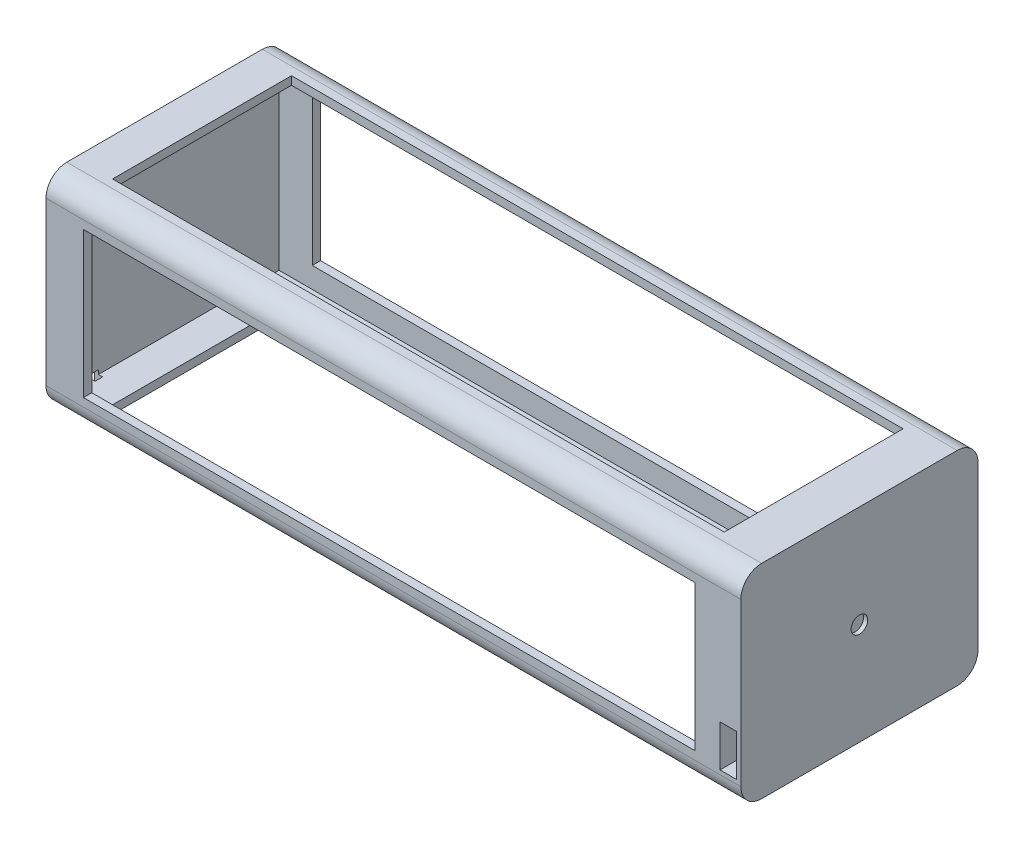
SolidWorks part; units mm, degrees
material "PET"
ref_plane "Спереди" through (0, 0, 0) normal (0, 0, 1) x (1, 0, 0)
ref_plane "Сверху" through (0, 0, 0) normal (0, 1, 0) x (1, 0, 0)
ref_plane "Справа" through (0, 0, 0) normal (1, 0, 0) x (0, 0, -1)
sketch "Эскиз1" plane through (0, 0, 0) normal (1, 0, 0) x (0, 0, -1)
  line L1 (26.5, -22.5) -> (-26.5, -22.5)
  line L2 (26.5, -22.5) -> (26.5, 22.5)
  line L3 (26.5, 22.5) -> (-26.5, 22.5)
  line L4 (-26.5, -22.5) -> (-26.5, 22.5)
  line L5 (26.5, -22.5) -> (-26.5, 22.5) construction
  line L6 (26.5, 22.5) -> (-26.5, -22.5) construction
  line L7 (28.5, -24.5) -> (-28.5, -24.5)
  line L8 (28.5, -24.5) -> (28.5, 24.5)
  line L9 (28.5, 24.5) -> (-28.5, 24.5)
  line L10 (-28.5, -24.5) -> (-28.5, 24.5)
  line L11 (28.5, -24.5) -> (-28.5, 24.5) construction
  line L12 (28.5, 24.5) -> (-28.5, -24.5) construction
  point P0 (0, 0)
  point P6 (0, 0)
  dimension "D1" = 53
  dimension "D2" = 45
  dimension "D3" = 57
  dimension "D4" = 49
extrude "Бобышка-Вытянуть1" add sketch "Эскиз1" against normal blind 5
ref_plane "Плоскость4" through (-5, 0, 0) normal (1, 0, 0) x (0, 0, -1)
sketch "Эскиз2" plane through (-5, 0, 0) normal (1, 0, 0) x (0, 0, -1)
  line L0 (26.5, 22.5) -> (-26.5, 22.5) construction
  line L1 (28.5, 24.5) -> (21.5, 24.5)
  line L2 (28.5, 24.5) -> (28.5, 22.5)
  line L3 (26.5, 22.5) -> (21.5, 22.5)
  line L4 (21.5, 24.5) -> (21.5, 22.5)
  line L5 (26.5, -22.5) -> (26.5, 22.5) construction
  line L6 (28.5, 24.5) -> (26.5, 24.5)
  line L7 (28.5, 24.5) -> (28.5, 17.5)
  line L8 (28.5, 17.5) -> (26.5, 17.5)
  line L9 (26.5, 22.5) -> (26.5, 17.5)
  line L10 (0, 34.0761) -> (0, -34.0192) construction
  line L11 (38.3689, 0) -> (-37.9997, 0) construction
  line L12 (-28.5, 24.5) -> (-28.5, 17.5)
  line L13 (-28.5, 17.5) -> (-26.5, 17.5)
  line L14 (-26.5, 22.5) -> (-26.5, 17.5)
  line L15 (-26.5, 22.5) -> (-21.5, 22.5)
  line L16 (-21.5, 24.5) -> (-21.5, 22.5)
  line L17 (-28.5, 24.5) -> (-21.5, 24.5)
  line L18 (-28.5, -24.5) -> (-21.5, -24.5)
  line L19 (-21.5, -24.5) -> (-21.5, -22.5)
  line L20 (-26.5, -22.5) -> (-21.5, -22.5)
  line L21 (-26.5, -22.5) -> (-26.5, -17.5)
  line L22 (-28.5, -17.5) -> (-26.5, -17.5)
  line L23 (-28.5, -24.5) -> (-28.5, -17.5)
  line L24 (28.5, -24.5) -> (28.5, -17.5)
  line L25 (28.5, -17.5) -> (26.5, -17.5)
  line L26 (26.5, -22.5) -> (26.5, -17.5)
  line L27 (26.5, -22.5) -> (21.5, -22.5)
  line L28 (21.5, -24.5) -> (21.5, -22.5)
  line L29 (28.5, -24.5) -> (21.5, -24.5)
  dimension "D1" = 7
  dimension "D2" = 7
extrude "Бобышка-Вытянуть2" add sketch "Эскиз2" against normal blind 147 contours L17 L12 L13 L14 L15 L16 | L23 L18 L19 L20 L21 L22 | L1 L4 L3 L9 L8 L7 | L27 L28 L29 L24 L25 L26
ref_plane "Плоскость5" through (-152, 0, 0) normal (1, 0, 0) x (0, 0, -1)
sketch "Эскиз3" plane through (-152, 0, 0) normal (1, 0, 0) x (0, 0, -1)
  line L1 (-26.5, -22.5) -> (26.5, -22.5)
  line L2 (-26.5, -22.5) -> (-26.5, 22.5)
  line L3 (-26.5, 22.5) -> (26.5, 22.5)
  line L4 (26.5, -22.5) -> (26.5, 22.5)
  line L5 (-26.5, -22.5) -> (26.5, 22.5) construction
  line L6 (-26.5, 22.5) -> (26.5, -22.5) construction
  line L7 (-28.5, -24.5) -> (28.5, -24.5)
  line L8 (-28.5, -24.5) -> (-28.5, 24.5)
  line L9 (-28.5, 24.5) -> (28.5, 24.5)
  line L10 (28.5, -24.5) -> (28.5, 24.5)
  line L11 (-28.5, -24.5) -> (28.5, 24.5) construction
  line L12 (-28.5, 24.5) -> (28.5, -24.5) construction
  point P0 (0, 0)
  point P7 (0, 0)
extrude "Бобышка-Вытянуть3" add sketch "Эскиз3" against normal blind 8
sketch "Эскиз5" plane through (0, 0, 0) normal (1, 0, 0) x (0, 0, -1)
  line L1 (28.5, -24.5) -> (-28.5, -24.5)
  line L2 (28.5, -24.5) -> (28.5, 24.5)
  line L3 (28.5, 24.5) -> (-28.5, 24.5)
  line L4 (-28.5, -24.5) -> (-28.5, 24.5)
  line L5 (28.5, -24.5) -> (-28.5, 24.5) construction
  line L6 (28.5, 24.5) -> (-28.5, -24.5) construction
  point P0 (0, 0)
extrude "Бобышка-Вытянуть4" add sketch "Эскиз5" along normal blind 1
sketch "Эскиз7" plane through (-160, 0, 0) normal (-1, 0, 0) x (0, 0, 1)
  line L1 (28.5, -24.5) -> (-28.5, -24.5)
  line L2 (28.5, -24.5) -> (28.5, 24.5)
  line L3 (28.5, 24.5) -> (-28.5, 24.5)
  line L4 (-28.5, -24.5) -> (-28.5, 24.5)
  line L5 (28.5, -24.5) -> (-28.5, 24.5) construction
  line L6 (28.5, 24.5) -> (-28.5, -24.5) construction
  point P0 (0, 0)
extrude "Бобышка-Вытянуть6" add sketch "Эскиз7" along normal blind 1
sketch "Эскиз8" plane through (-161, 0, 0) normal (-1, 0, 0) x (0, 0, 1)
  line L0 (-28.5, -24.5) -> (28.5, -24.5) construction
  line L1 (22.5, -24.5) -> (20.7, -24.5)
  line L2 (22.5, -24.5) -> (22.5, -21.5)
  line L3 (22.5, -21.5) -> (20.7, -21.5)
  line L4 (20.7, -24.5) -> (20.7, -21.5)
  line L6 (18.7, -24.5) -> (16.9, -24.5)
  line L7 (18.7, -24.5) -> (18.7, -21.5)
  line L8 (18.7, -21.5) -> (16.9, -21.5)
  line L9 (16.9, -24.5) -> (16.9, -21.5)
  line L10 (14.9, -24.5) -> (14.4, -24.5)
  line L11 (14.9, -24.5) -> (14.9, -23)
  line L12 (14.9, -23) -> (14.4, -23)
  line L13 (14.4, -24.5) -> (14.4, -23)
  line L14 (13.4, -24.5) -> (12.9, -24.5)
  line L15 (13.4, -24.5) -> (13.4, -23)
  line L16 (13.4, -23) -> (12.9, -23)
  line L17 (12.9, -24.5) -> (12.9, -23)
  line L18 (11.9, -24.5) -> (11.4, -24.5)
  line L19 (11.9, -24.5) -> (11.9, -23)
  line L20 (11.9, -23) -> (11.4, -23)
  line L21 (11.4, -24.5) -> (11.4, -23)
  line L22 (10.4, -24.5) -> (9.9, -24.5)
  line L23 (10.4, -24.5) -> (10.4, -23)
  line L24 (10.4, -23) -> (9.9, -23)
  line L25 (9.9, -24.5) -> (9.9, -23)
  line L26 (8.9, -24.5) -> (8.4, -24.5)
  line L27 (8.9, -24.5) -> (8.9, -23)
  line L28 (8.9, -23) -> (8.4, -23)
  line L29 (8.4, -24.5) -> (8.4, -23)
  line L30 (7.4, -24.5) -> (6.9, -24.5)
  line L31 (7.4, -24.5) -> (7.4, -23)
  line L32 (7.4, -23) -> (6.9, -23)
  line L33 (6.9, -24.5) -> (6.9, -23)
  line L34 (5.9, -24.5) -> (5.4, -24.5)
  line L35 (5.9, -24.5) -> (5.9, -23)
  line L36 (5.9, -23) -> (5.4, -23)
  line L37 (5.4, -24.5) -> (5.4, -23)
  dimension "D1" = 1.8
  dimension "D2" = 3
  dimension "D3" = 6
  dimension "D4" = 2
  dimension "D5" = 1
  dimension "D6" = 1
  dimension "D7" = 1
  dimension "D8" = 1
  dimension "D9" = 1
  dimension "D10" = 1
  dimension "D11" = 2
  dimension "D12" = 0.5
  dimension "D13" = 1.5
extrude "Вырез-Вытянуть1" cut sketch "Эскиз8" against normal blind 2
sketch "Эскиз9" plane through (1, 0, 0) normal (1, 0, 0) x (0, 0, -1)
  line L0 (28.5, 24.5) -> (-28.5, 24.5) construction
  line L1 (24.5, -20.5) -> (-24.5, -20.5)
  line L2 (24.5, -20.5) -> (24.5, 8.5)
  line L3 (24.5, 20.5) -> (-24.5, 20.5)
  line L4 (-24.5, -20.5) -> (-24.5, -18.5)
  line L5 (24.5, -20.5) -> (-24.5, 20.5) construction
  line L6 (24.5, 20.5) -> (-24.5, -20.5) construction
  line L7 (28.5, -24.5) -> (28.5, 24.5) construction
  line L8 (24.5, 18.5) -> (28.5, 18.5)
  line L9 (28.5, -24.5) -> (-28.5, -24.5)
  line L10 (28.5, -24.5) -> (28.5, 8.5)
  line L11 (28.5, 24.5) -> (-28.5, 24.5)
  line L12 (-28.5, -24.5) -> (-28.5, -18.5)
  line L13 (28.5, -24.5) -> (-28.5, 24.5) construction
  line L14 (28.5, 24.5) -> (-28.5, -24.5) construction
  line L15 (24.5, 8.5) -> (28.5, 8.5)
  line L16 (0, 32.8484) -> (0, -30.0594) construction
  line L17 (-33.5411, 0) -> (36.5459, 0) construction
  line L18 (24.5, 18.5) -> (24.5, 20.5)
  line L19 (28.5, 18.5) -> (28.5, 24.5)
  line L20 (1.3, -18.5) -> (-1.3, -18.5)
  line L21 (1.3, 8.5) -> (-1.3, 8.5)
  line L22 (1.3, 8.5) -> (1.3, 18.5)
  line L23 (1.3, 18.5) -> (-1.3, 18.5)
  line L24 (-1.3, 8.5) -> (-1.3, 18.5)
  line L25 (-1.3, -8.5) -> (-1.3, -18.5)
  line L26 (1.3, -8.5) -> (-1.3, -8.5)
  line L27 (1.3, -8.5) -> (1.3, -18.5)
  line L28 (-24.5, -8.5) -> (-28.5, -8.5)
  line L29 (-24.5, -18.5) -> (-28.5, -18.5)
  line L30 (-28.5, -8.5) -> (-28.5, 24.5)
  line L31 (-24.5, -8.5) -> (-24.5, 20.5)
  point P0 (0, 0)
  point P10 (0, 0)
  dimension "D1" = 4
  dimension "D2" = 4
  dimension "D3" = 10
  dimension "D4" = 6
  dimension "D5" = 2.6
  dimension "D6" = 10
  dimension "D7" = 8.5
  dimension "D8" = 1.3
extrude "Бобышка-Вытянуть7" add sketch "Эскиз9" along normal blind 4
sketch "Эскиз10" plane through (5, 0, 0) normal (1, 0, 0) x (0, 0, -1)
  line L1 (28.5, -24.5) -> (-28.5, -24.5)
  line L2 (28.5, -24.5) -> (28.5, 24.5)
  line L3 (28.5, 24.5) -> (-28.5, 24.5)
  line L4 (-28.5, -24.5) -> (-28.5, 24.5)
  line L5 (28.5, -24.5) -> (-28.5, 24.5) construction
  line L6 (28.5, 24.5) -> (-28.5, -24.5) construction
  point P0 (0, 0)
extrude "Бобышка-Вытянуть8" add sketch "Эскиз10" along normal blind 1
sketch "Эскиз11" plane through (6, 0, 0) normal (1, 0, 0) x (0, 0, -1)
  circle A0 centre (0, 0) radius 2
  dimension "D1" = 4
extrude "Вырез-Вытянуть2" cut sketch "Эскиз11" against normal blind 6
fillet "Скругление2" radius 5 4 edges at (-77.5, -24.5, 28.5) (-77.5, -24.5, -28.5) (-77.5, 24.5, -28.5) (-77.5, 24.5, 28.5)
